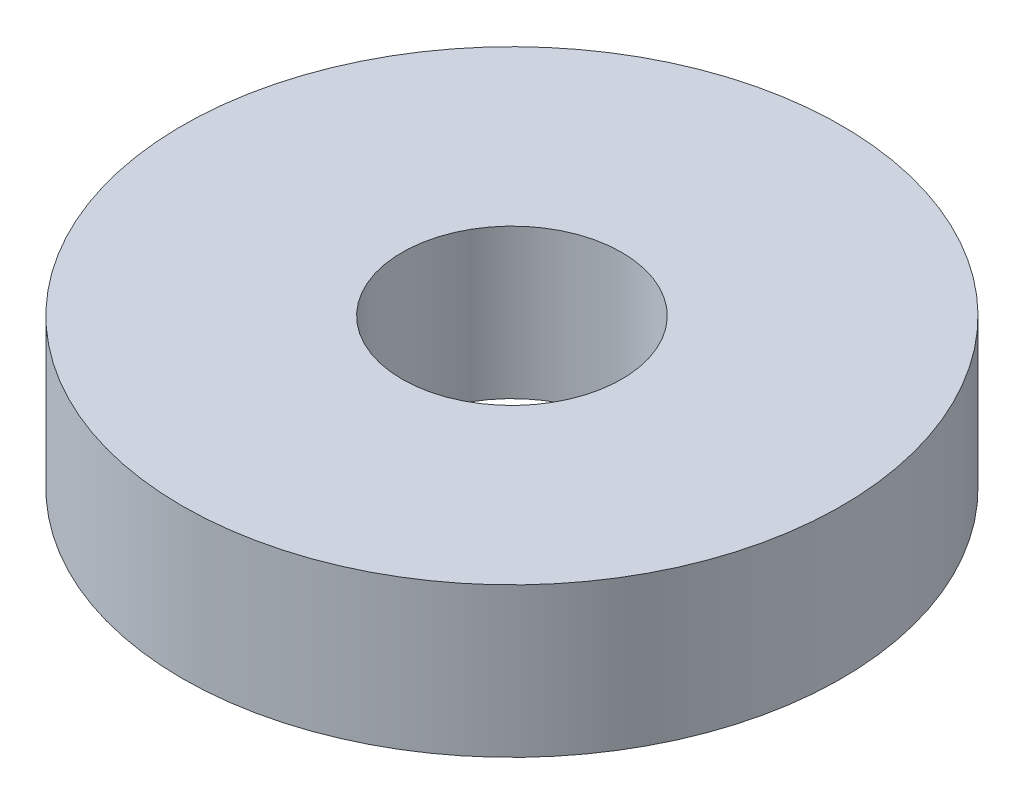
SolidWorks part; units mm, degrees
material "聚脂树脂"
ref_plane "前视基准面" through (0, 0, 0) normal (0, 0, 1) x (1, 0, 0)
ref_plane "上视基准面" through (0, 0, 0) normal (0, 1, 0) x (1, 0, 0)
ref_plane "右视基准面" through (0, 0, 0) normal (1, 0, 0) x (0, 0, -1)
other "Configuration Table"
sketch "草图1" plane through (0, 0, 0) normal (0, 1, 0) x (1, 0, 0)
  circle A0 centre (0, 0) radius 2.5
  circle A1 centre (0, 0) radius 7.5
  dimension "D1" = 5
  dimension "D2" = 15
extrude "凸台-拉伸1" add sketch "草图1" along normal blind 3.4
